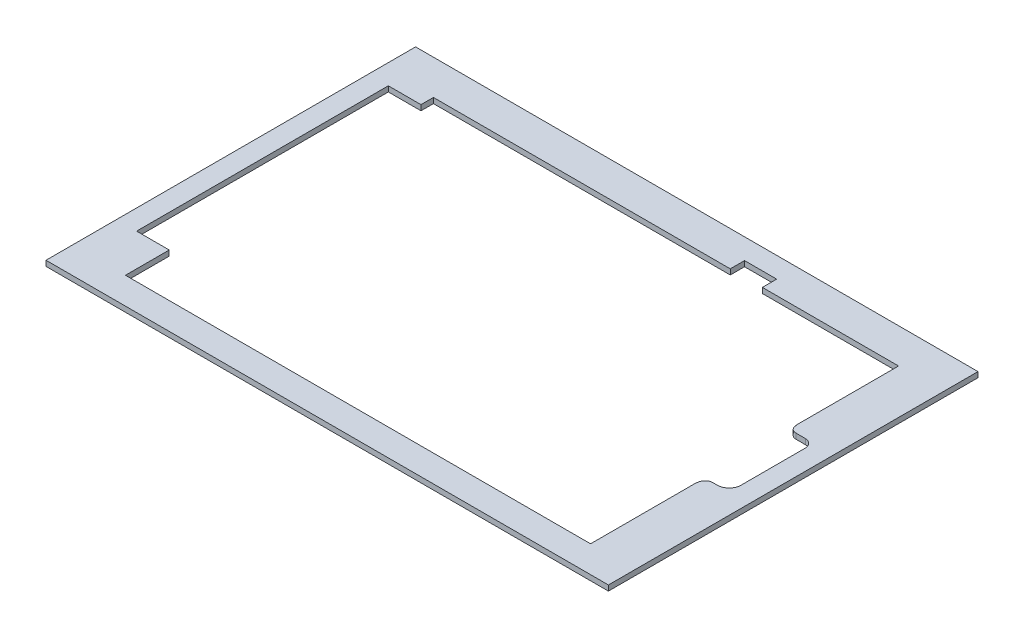
SolidWorks part; units mm, degrees
ref_plane "Front Plane" through (0, 0, 0) normal (0, 0, 1) x (1, 0, 0)
ref_plane "Top Plane" through (0, 0, 0) normal (0, 1, 0) x (1, 0, 0)
ref_plane "Right Plane" through (0, 0, 0) normal (1, 0, 0) x (0, 0, -1)
sketch "Sketch1" plane through (0, 0, 0) normal (0, 1, 0) x (1, 0, 0)
  line L1 (52.5, -34.5) -> (-52.5, -34.5)
  line L2 (52.5, -34.5) -> (52.5, 34.5)
  line L3 (52.5, 34.5) -> (-52.5, 34.5)
  line L4 (-52.5, -34.5) -> (-52.5, 34.5)
  line L5 (52.5, -34.5) -> (-52.5, 34.5) construction
  line L6 (52.5, 34.5) -> (-52.5, -34.5) construction
  point P0 (0, 0)
  dimension "D1" = 105
  dimension "D2" = 69
extrude "Boss-Extrude1" add sketch "Sketch1" along normal blind 5
extrude "Cut-Extrude1" cut sketch "Sketch2" against normal through all
sketch "Sketch2" plane through (17.0721, 0, 5.1034) normal (0, -1, 0) x (-1, 0, 0)
  line L0 (59.7281, 33.0909) -> (-27.1079, 33.0909)
  line L1 (-27.1079, 33.0909) -> (-27.1079, -24.4081)
  line L2 (-27.1079, -24.4081) -> (59.7281, -24.4081)
  line L3 (59.7281, -24.4081) -> (59.7281, 33.0909)
  line L8 (-26.1079, -23.4081) -> (58.7281, -23.4081) construction
  line L9 (-26.1079, 32.0909) -> (-26.1079, -23.4081) construction
  line L10 (58.7281, 32.0909) -> (-26.1079, 32.0909) construction
  line L11 (58.7281, -23.4081) -> (58.7281, 32.0909) construction
extrude "Cut-Extrude2" cut sketch "Sketch3" against normal blind 1
sketch "Sketch3" plane through (17.0721, 0, 5.1034) normal (0, -1, 0) x (-1, 0, 0)
  line L1 (59.8221, 30.7659) -> (54.5248, 30.7659)
  line L2 (59.8221, 30.7659) -> (59.8221, -16.2341) construction
  line L3 (59.8221, -16.2341) -> (54.5248, -16.2341)
  line L8 (65.3221, 30.2659) -> (60.3221, 30.2659) construction
  line L9 (60.3221, 30.2659) -> (60.3221, -15.7341) construction
  line L10 (60.3221, -15.7341) -> (65.3221, -15.7341) construction
  line L11 (65.3221, -15.7341) -> (65.3221, 30.2659) construction
  line L12 (54.5248, 30.7659) -> (54.5248, -16.2341)
  line L20 (65.8221, 30.7659) -> (59.8221, 30.7659)
  line L21 (59.8221, 30.7659) -> (59.8221, -16.2341) construction
  line L22 (59.8221, -16.2341) -> (65.8221, -16.2341)
  line L23 (65.8221, -16.2341) -> (65.8221, 30.7659)
extrude "Cut-Extrude3" cut sketch "Sketch4" against normal blind 1
sketch "Sketch4" plane through (17.0721, 0, 5.1034) normal (0, -1, 0) x (-1, 0, 0)
  line L8 (69.5721, -29.3966) -> (69.5721, 39.6034)
  line L9 (69.5721, 39.6034) -> (-35.4279, 39.6034)
  line L10 (-35.4279, 39.6034) -> (-35.4279, -29.3966)
  line L11 (-35.4279, -29.3966) -> (69.5721, -29.3966)
  line L16 (3.8121, 35.2559) -> (-1.1879, 35.2559)
  line L17 (-1.1879, 35.2559) -> (-1.1879, 32.7559)
  line L18 (-1.1879, 32.7559) -> (3.8121, 32.7559)
  line L19 (3.8121, 32.7559) -> (3.8121, 35.2559)
  line L28 (4.3121, 35.7559) -> (-1.6879, 35.7559)
  line L29 (-1.6879, 35.7559) -> (-1.6879, 32.2559)
  line L30 (-1.6879, 32.2559) -> (4.3121, 32.2559)
  line L31 (4.3121, 32.2559) -> (4.3121, 35.7559)
extrude "Cut-Extrude4" cut sketch "Sketch5" against normal through all contours L3 L2 A3 L5 A2 L4 | L2 L3 L4 A4 L6 A5
sketch "Sketch5" plane through (17.0721, 0, 5.1034) normal (0, -1, 0) x (-1, 0, 0)
  line L2 (-27.1779, 33.1034) -> (-27.1779, 13.8376)
  line L3 (-27.1779, 5.1034) -> (-31.6779, 5.1034) construction
  line L4 (-31.6779, -0.8966) -> (-31.6779, 11.1034)
  line L5 (-30.1159, 12.6653) -> (-28.3501, 12.6653)
  line L6 (-29.4785, -3.0961) -> (-28.6478, -3.0961)
  line L7 (-27.1779, 5.1034) -> (-27.1779, 13.8376) construction
  line L8 (-27.1779, -4.566) -> (-18.8659, -4.566)
  line L9 (-27.1779, -4.566) -> (-27.1779, 5.1034)
  line L10 (-27.1779, 13.8376) -> (-18.8659, 13.8376)
  line L11 (-18.8659, -4.566) -> (-18.8659, 13.8376)
  line L12 (-27.1779, 13.8376) -> (-27.1779, 5.1034) construction
  line L13 (-27.1779, 5.1034) -> (-27.1779, -22.8966)
  arc A2 (-31.6779, 11.1034) -> (-30.1159, 12.6653) centre (-30.1159, 11.1034) cw
  arc A3 (-28.3501, 12.6653) -> (-27.1779, 13.8376) centre (-28.3501, 13.8376) ccw
  arc A4 (-31.6779, -0.8966) -> (-29.4785, -3.0961) centre (-29.4785, -0.8966) ccw
  arc A5 (-28.6478, -3.0961) -> (-27.1779, -4.566) centre (-28.6478, -4.566) cw
  point P8 (-31.6779, 5.1034)
sketch "Sketch6" plane through (0, 5, 0) normal (0, 1, 0) x (1, 0, 0)
  line L4 (-52.5, 34.5) -> (-52.5, -34.5)
  line L5 (-52.5, -34.5) -> (52.5, -34.5)
  line L6 (52.5, -34.5) -> (52.5, 34.5)
  line L7 (52.5, 34.5) -> (-52.5, 34.5)
  line L8 (-52.5, 34.5) -> (-52.5, -34.5)
  line L9 (-52.5, -34.5) -> (52.5, -34.5)
  line L10 (52.5, -34.5) -> (52.5, 34.5)
  line L11 (52.5, 34.5) -> (-52.5, 34.5)
  dimension "D1" = 0
extrude "Cut-Extrude5" cut sketch "Sketch6" against normal blind 4
